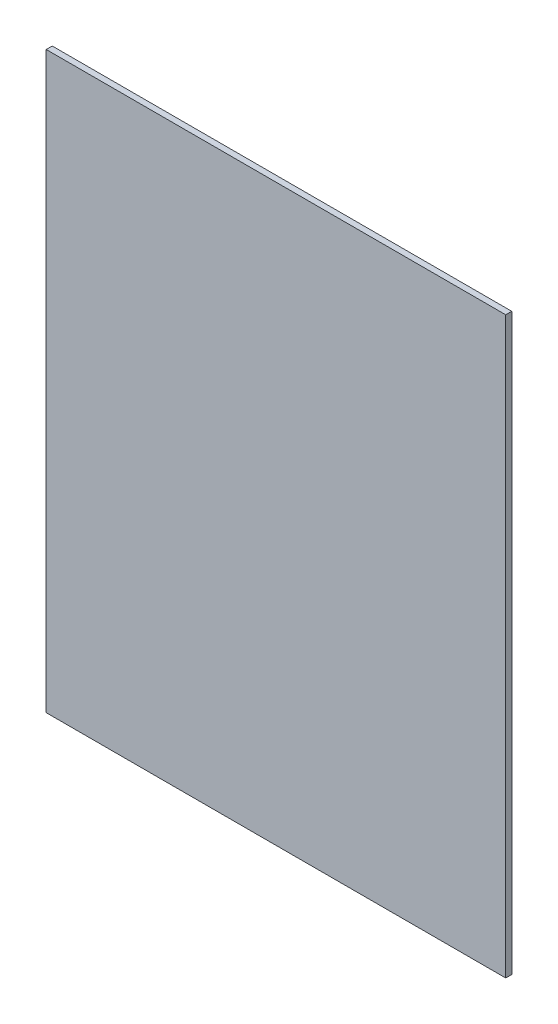
SolidWorks part; units mm, degrees
ref_plane "Front Plane" through (0, 0, 0) normal (0, 0, 1) x (1, 0, 0)
ref_plane "Top Plane" through (0, 0, 0) normal (0, 1, 0) x (1, 0, 0)
ref_plane "Right Plane" through (0, 0, 0) normal (1, 0, 0) x (0, 0, -1)
sketch "Sketch1" plane through (0, 0, 0) normal (0, 0, 1) x (1, 0, 0)
  line L1 (-76, -95) -> (76, -95)
  line L2 (-76, -95) -> (-76, 95)
  line L3 (-76, 95) -> (76, 95)
  line L4 (76, -95) -> (76, 95)
  line L5 (-76, -95) -> (76, 95) construction
  line L6 (-76, 95) -> (76, -95) construction
  point P0 (0, 0)
  dimension "D1" = 190
  dimension "D2" = 152
extrude "Boss-Extrude1" add sketch "Sketch1" along normal blind 2
